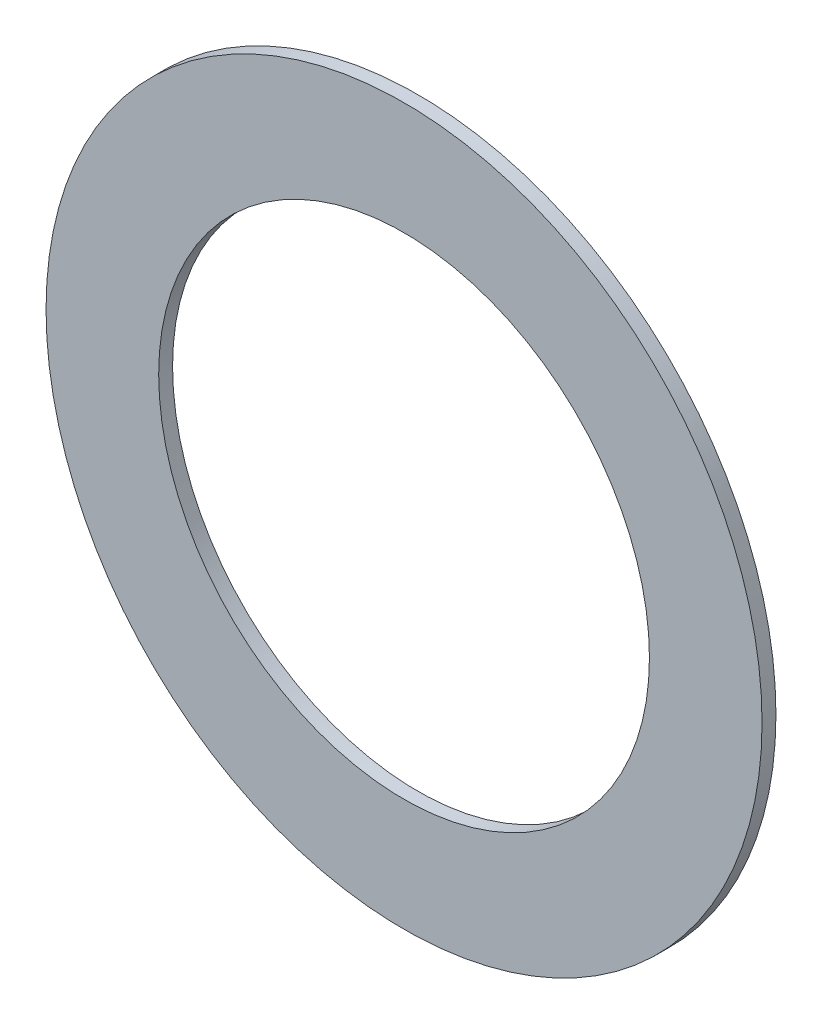
SolidWorks part; units mm, degrees
ref_plane "Ebene vorne" through (0, 0, 0) normal (0, 0, 1) x (1, 0, 0)
ref_plane "Ebene oben" through (0, 0, 0) normal (0, 1, 0) x (1, 0, 0)
ref_plane "Ebene rechts" through (0, 0, 0) normal (1, 0, 0) x (0, 0, -1)
sketch "Skizze1" plane through (0, 0, 0) normal (0, 0, 1) x (1, 0, 0)
  circle A0 centre (0, 0) radius 25.75
  circle A1 centre (0, 0) radius 17.65
  dimension "D1" = 51.5
  dimension "D2" = 35.3
extrude "Aufsatz-Linear austragen1" add sketch "Skizze1" along normal blind 1
